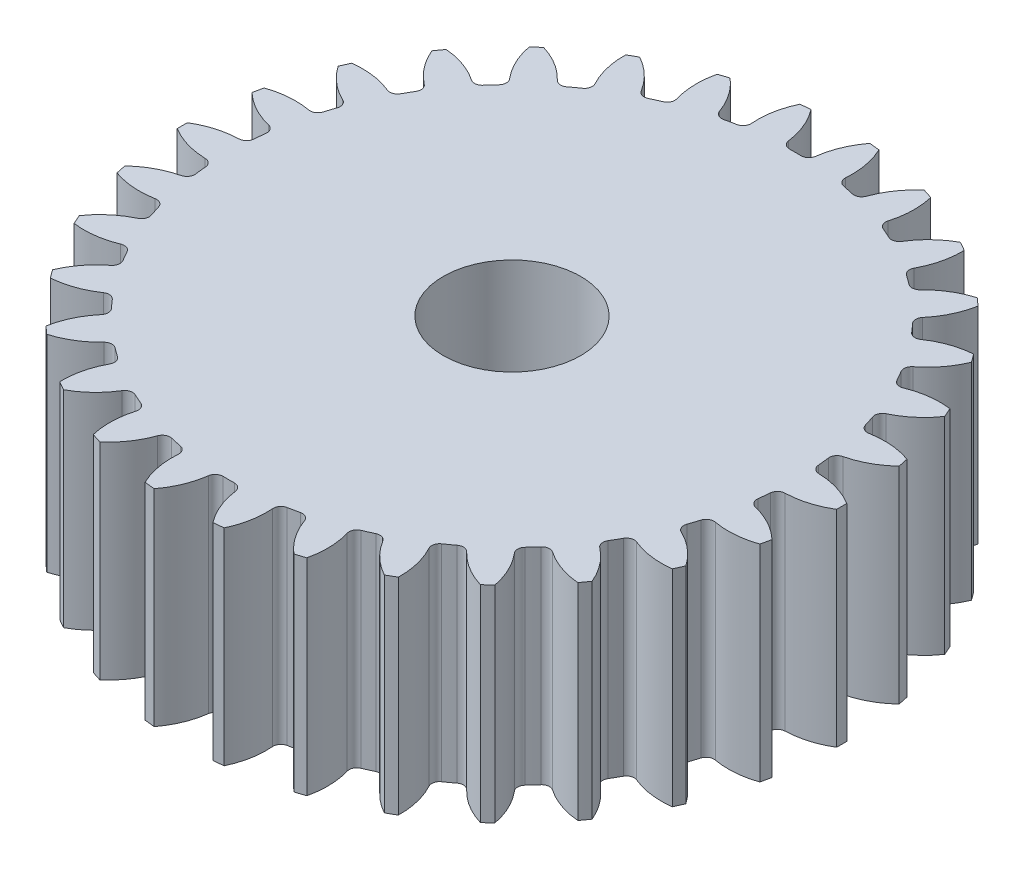
SolidWorks part; units mm, degrees
ref_plane "Front Plane" through (0, 0, 0) normal (0, 0, 1) x (1, 0, 0)
ref_plane "Top Plane" through (0, 0, 0) normal (0, 1, 0) x (1, 0, 0)
ref_plane "Right Plane" through (0, 0, 0) normal (1, 0, 0) x (0, 0, -1)
sketch "Sketch1" plane through (0, 0, 0) normal (0, 1, 0) x (1, 0, 0)
  circle A0 centre (0, 0) radius 5
  circle A1 centre (0, 0) radius 24
  dimension "D1" = 10
  dimension "D2" = 48
extrude "Boss-Extrude1" add sketch "Sketch1" along normal blind 15
sketch "Sketch2" plane through (0, 0, 0) normal (0, 1, 0) x (1, 0, 0)
  line L0 (0, 0) -> (0, 24) construction
  line L1 (0, 0) -> (-0.936, 20.6037) construction
  line L2 (0, 18.8178) -> (-5.466, 33.8354) construction
  arc A0 (0.936, 20.6037) -> (-0.936, 20.6037) centre (0, 0) ccw
  arc A1 (1.3273, 22.4608) -> (-1.3273, 22.4608) centre (0, 0) ccw construction
  arc A2 (2.1375, 23.9046) -> (-2.1375, 23.9046) centre (0, 0) ccw
  arc A3 (-2.1375, 23.9046) -> (-0.936, 20.6037) centre (-6.8037, 20.3372) cw
  arc A4 (2.1375, 23.9046) -> (0.936, 20.6037) centre (6.8037, 20.3372) ccw
  point P14 (-2.733, 26.3266)
  point P17 (-1.2842, 22.3461)
  dimension "D1" = 48
  dimension "D2" = 45
  dimension "D3" = 3.375
  dimension "D4" = 20
  dimension "D5" = 2.6562
extrude "Cut-Extrude1" cut sketch "Sketch2" along normal blind 15 contours A2 A3 A0 A4
fillet "Fillet1" radius 0.57 2 edges at (0.936, 7.5, -20.6037) (-0.936, 7.5, -20.6037)
pattern_circular "CirPattern1" count 30 over 360 about axis through (0, 0, 0) along (0, 1, 0) of "Fillet1", "Cut-Extrude1"
scale "Scale1" scale about centroid uniform scaling yes scale factor 10
equation "\"num_teeth\"= 30"
equation "\"outer_diameter\"= ( \"num_teeth\" + 2 ) * \"module\""
equation "\"module\"= 1.5"
equation "\"pitch_diameter\"= \"num_teeth\" * \"module\""
equation "\"arc_length\"= \"module\" * pi / 2 + \"backlash\""
equation "\"backlash\"= 0.2 * \"module\""
equation "\"Tooth_depth\"= IIF ( \"module\" <= 1.25 , \"module\" * 2.4 , \"module\" * 2.25 )"
equation "\"bore_diameter\"= 10mm"
equation "\"D2@Sketch1\"=\"outer_diameter\""
equation "\"D1@Sketch2\"=\"outer_diameter\""
equation "\"D2@Sketch2\"=\"pitch_diameter\""
equation "\"D3@Sketch2\"=\"Tooth_depth\""
equation "\"pitch_angle\"=20"
equation "\"D4@Sketch2\"=\"pitch_angle\""
equation "\"D5@Sketch2\"=\"arc_length\""
equation "\"fillet_radius\"= 0.38 * \"module\""
equation "\"D1@Fillet1\"=\"fillet_radius\""
equation "\"D1@CirPattern1\"=\"num_teeth\""
